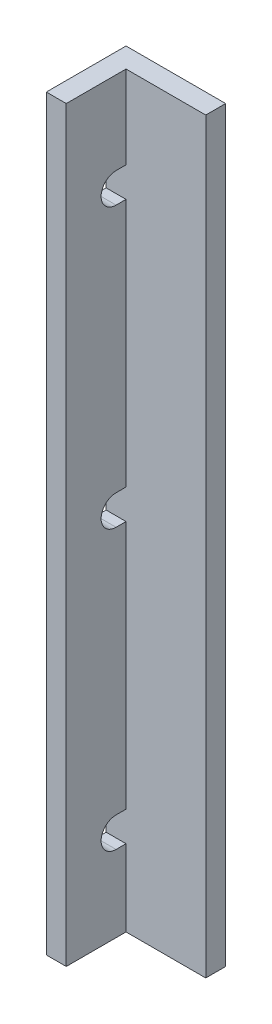
SolidWorks part; units mm, degrees
ref_plane "Plan de face" through (0, 0, 0) normal (0, 0, 1) x (1, 0, 0)
ref_plane "Plan de dessus" through (0, 0, 0) normal (0, 1, 0) x (1, 0, 0)
ref_plane "Plan de droite" through (0, 0, 0) normal (1, 0, 0) x (0, 0, -1)
sketch "Esquisse2" plane through (0, 0, 0) normal (0, 1, 0) x (1, 0, 0)
  line L0 (0, 0) -> (0, 8)
  line L1 (0, 8) -> (10, 8)
  line L2 (10, 8) -> (10, 6)
  line L3 (10, 6) -> (2, 6)
  line L4 (2, 6) -> (2, 0)
  line L5 (2, 0) -> (0, 0)
  dimension "D1" = 8
  dimension "D2" = 10
  dimension "D3" = 2
  dimension "D4" = 2
extrude "Boss.-Extru.1" add sketch "Esquisse2" along normal blind 75 contours L1 L2 L3 L4 L5 L0
sketch "Esquisse3" plane through (2, 0, 0) normal (1, 0, 0) x (0, 0, -1)
  line L2 (6, 38.6728) -> (6, 35.6728)
  line L3 (6, 75) -> (6, 0) construction
  line L4 (6, 38.6728) -> (5, 38.6728)
  line L5 (6, 35.6728) -> (5, 35.6728)
  line L6 (6, 23.1728) -> (6, 35.6728) construction
  line L7 (6, 38.6728) -> (6, 51.1728) construction
  line L8 (6, 23.1728) -> (0, 23.1728) construction
  line L9 (6, 51.1728) -> (0.7645, 51.1728) construction
  line L10 (6, 63.6728) -> (5, 63.6728)
  line L11 (6, 66.6728) -> (5, 66.6728)
  line L12 (6, 63.6728) -> (6, 66.6728)
  line L13 (6, 7.6728) -> (5, 7.6728)
  line L14 (6, 7.6728) -> (6, 10.6728)
  line L15 (6, 10.6728) -> (5, 10.6728)
  arc A0 (5, 38.6728) -> (5, 35.6728) centre (5, 37.1728) ccw
  arc A1 (5, 63.6728) -> (5, 66.6728) centre (5, 65.1728) cw
  arc A2 (5, 7.6728) -> (5, 10.6728) centre (5, 9.1728) cw
  point P5 (6, 37.1728)
  point P22 (0, 0)
  point P23 (6, 9.1728)
  dimension "D1" = 3
  dimension "D2" = 1
  dimension "D4" = 1.5
  dimension "D3" = 1
  dimension "D5" = 12.5
  dimension "D6" = 12.5
extrude "Enlèv. mat.-Extru.9" cut sketch "Esquisse3" along normal blind 1 and the other way blind 3
